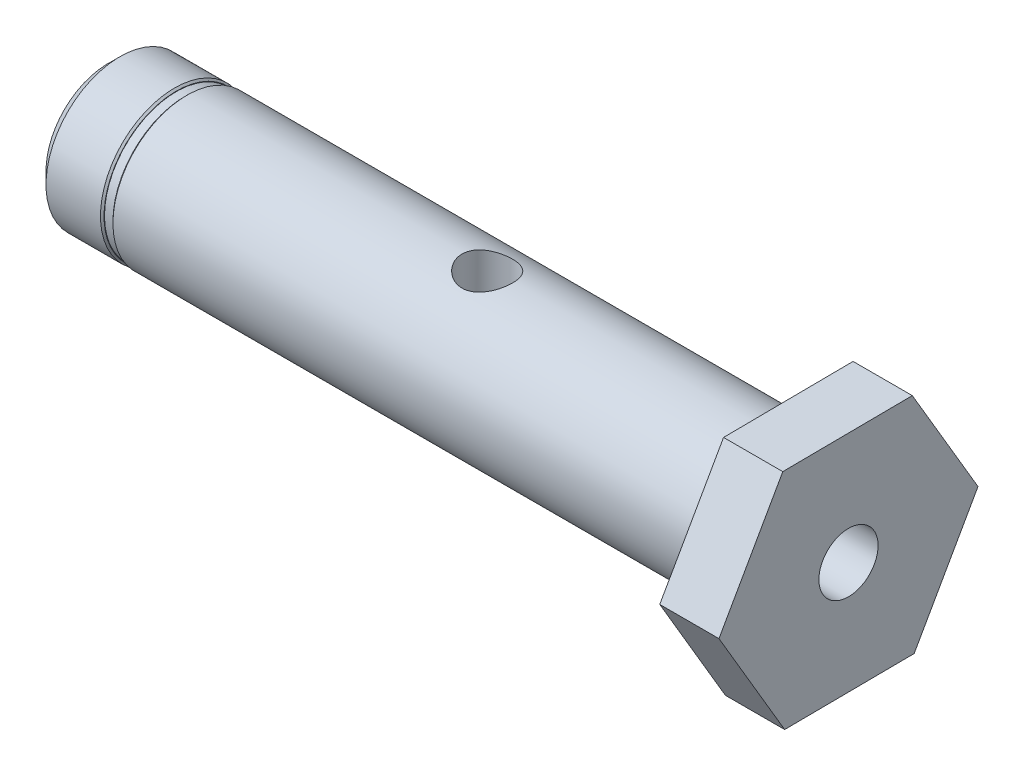
SolidWorks part; units mm, degrees
ref_plane "Front Plane" through (0, 0, 0) normal (0, 0, 1) x (1, 0, 0)
ref_plane "Top Plane" through (0, 0, 0) normal (0, 1, 0) x (1, 0, 0)
ref_plane "Right Plane" through (0, 0, 0) normal (1, 0, 0) x (0, 0, -1)
sketch "Sketch1" plane through (0, 0, 0) normal (1, 0, 0) x (0, 0, -1)
  circle A0 centre (0, 0) radius 12.5
  dimension "D1" = 25
extrude "Boss-Extrude1" add sketch "Sketch1" along normal blind 115
chamfer "Chamfer1" distance 2 angle 45 1 edges at (0, 0, -12.5)
ref_plane "Plane1" through (0, 0, 0) normal (0, 0, 1) x (1, 0, 0)
sketch "Sketch2" plane through (0, 0, 0) normal (0, 0, 1) x (1, 0, 0)
  line L0 (-5.7794, 0) -> (117.7794, 0) construction
sketch "Sketch3" plane through (115, 0, 0) normal (1, 0, 0) x (0, 0, -1)
  line L1 (11.0935, -18.8472) -> (21.8689, 0.1837)
  line L2 (21.8689, 0.1837) -> (10.7754, 19.0308)
  line L3 (10.7754, 19.0308) -> (-11.0935, 18.8472)
  line L4 (-11.0935, 18.8472) -> (-21.8689, -0.1837)
  line L5 (-21.8689, -0.1837) -> (-10.7754, -19.0308)
  line L6 (-10.7754, -19.0308) -> (11.0935, -18.8472)
  circle A0 centre (0, 0) radius 18.9397 construction
extrude "Boss-Extrude2" add sketch "Sketch3" along normal blind 10
hole_wizard "Ø8.0mm Dowel Hole1" positions "Sketch4" profile "Sketch6" hole size "Ø8.0" standard "ISO"
sketch "Sketch4" plane through (125, 0, 0) normal (1, 0, 0) x (0, 0, -1)
  point P0 (0, 0)
sketch "Sketch6" plane through (125, 0, 0) normal (0, 1, 0) x (0, 0, -1)
  line L0 (0, 0) -> (0, 72.5537)
  line L1 (0, 72.5537) -> (4.25, 70)
  line L2 (4.25, 70) -> (4.25, 0)
  line L5 (4.25, 0) -> (0, 0)
  line L10 (0, 72.5537) -> (-4.25, 70) construction
  line L11 (0, -6.35) -> (0, 107.95) construction
  dimension "Hole Dia." = 8.5
  dimension "Hole Depth" = 70
  dimension "Drill Angle" = 118
sketch "Sketch7" plane through (125, 0, 0) normal (1, 0, 0) x (0, 0, -1)
  circle A0 centre (0, 0) radius 5
  circle A1 centre (0, 0) radius 4.25
  dimension "D1" = 10
extrude "Cut-Extrude1" cut sketch "Sketch7" against normal blind 13
sketch "Sketch10" plane through (0, 0, 0) normal (0, 1, 0) x (1, 0, 0)
  line L0 (-5.7794, 0) -> (117.7794, 0) construction
  line L1 (115, 12.5) -> (115, -12.5) construction
  circle A0 centre (64, 0) radius 4.25
  dimension "D1" = 8.5
  dimension "D2" = 51
extrude "Cut-Extrude2" cut sketch "Sketch10" against normal through all both and the other way through all
sketch "Sketch11" plane through (0, 0, 0) normal (0, 0, 1) x (1, 0, 0)
  line L0 (13, 16.8873) -> (13, 12.125)
  line L1 (115, 12.5) -> (115, -12.5) construction
  line L2 (13, 16.8873) -> (11.5, 16.8873)
  line L3 (11.5, 16.8873) -> (11.5, 12.125)
  line L4 (11.5, 12.125) -> (13, 12.125)
  line L5 (59.75, 12.5) -> (2, 12.5) construction
  dimension "D1" = 102
  dimension "D2" = 1.5
  dimension "D3" = 0.375
revolve "Cut-Revolve3" cut sketch "Sketch11" angle 360 about L0
chamfer "Chamfer2" distance 0.3 angle 45 1 edges at (13, 0, 12.5)
chamfer "Chamfer3" distance 0.3 angle 45 1 edges at (11.5, 0, -12.5)
